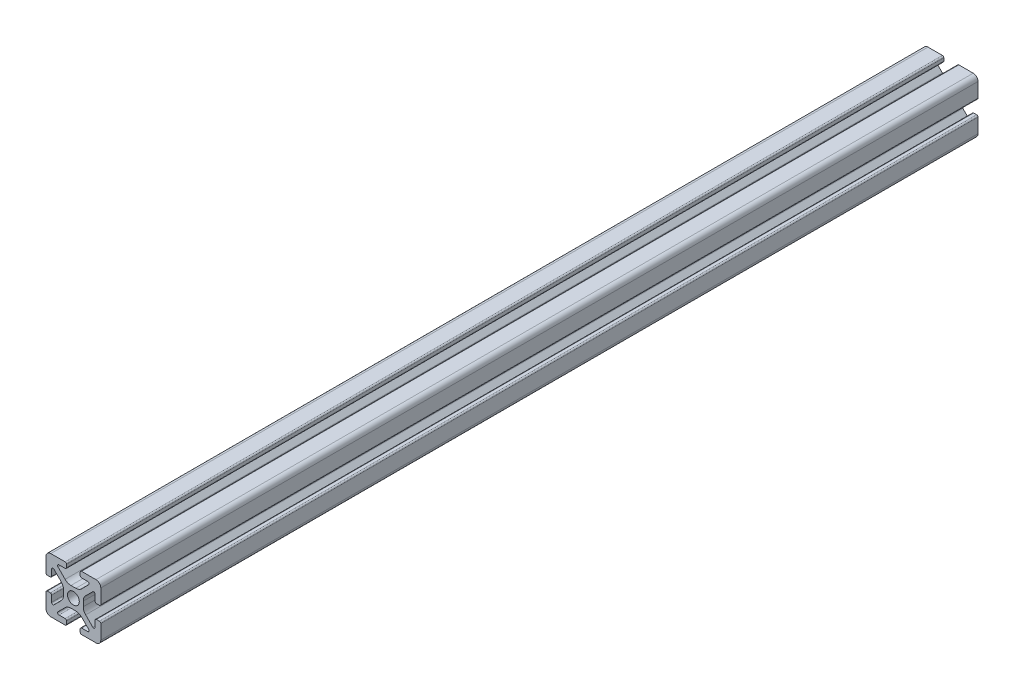
SolidWorks part; units mm, degrees
material "1060 Alloy"
ref_plane "Front Plane" through (0, 0, 0) normal (0, 0, 1) x (1, 0, 0)
ref_plane "Top Plane" through (0, 0, 0) normal (0, 1, 0) x (1, 0, 0)
ref_plane "Right Plane" through (0, 0, 0) normal (1, 0, 0) x (0, 0, -1)
sketch "Sketch2" plane through (0, 0, 0) normal (0, 0, 1) x (1, 0, 0)
  line L0 (0, 10) -> (0, -10) construction
  line L1 (-10, 0) -> (10, 0) construction
  line L2 (2.5, -10) -> (10, -10)
  line L3 (10, -10) -> (10, -2.5)
  line L4 (2.5, -10) -> (2.5, -7.9246)
  line L5 (2.5, -7.9246) -> (6.4571, -7.9246)
  line L6 (6.4571, -7.9246) -> (2.1325, -3.6)
  line L7 (0, 0) -> (10, -10) construction
  line L8 (10, -2.5) -> (7.9246, -2.5)
  line L9 (7.9246, -2.5) -> (7.9246, -6.4571)
  line L10 (7.9246, -6.4571) -> (3.6, -2.1325)
  line L11 (5.7623, -4.2948) -> (4.2948, -5.7623) construction
  circle A0 centre (0, 0) radius 2.15
  arc A1 (5.25, -7.9246) -> (5.6036, -7.0711) centre (5.25, -7.4246) ccw construction
  point P8 (0, -3.6)
  point P16 (5.0286, -5.0286)
  dimension "Center Hole Diameter" = 4.3
  dimension "D3" = 0.5
  dimension "Rail Height" = 20
  dimension "Rail Width" = 20
  dimension "T-Slot Width" = 5
  dimension "Slot Depth" = 6.4
  dimension "Slot Inner Width" = 11.5
sketch "Sketch3" plane through (0, 0, 0) normal (1, 0, 0) x (0, 0, -1)
  line L0 (-110, -10) -> (110, -10) construction
  line L1 (-84.6, 0) -> (84.6, 0) construction
  line L2 (0, 10) -> (0, -10) construction
  line L3 (0, 10) -> (0, -10) construction
  point P6 (-84.6, 0)
  point P8 (84.6, 0)
  dimension "Length" = 220
  dimension "D1" = 25.4
sketch "Sketch4" plane through (0, 0, 0) normal (0, 0, 1) x (1, 0, 0)
  line L0 (3, -10) -> (8.25, -10)
  line L1 (2.5, -10) -> (10, -10) construction
  line L2 (2.5, -10) -> (2.5, -7.9246) construction
  line L3 (2.5, -7.9246) -> (6.4571, -7.9246) construction
  line L4 (2.5, -8.4246) -> (2.5, -9.5)
  line L5 (3, -7.9246) -> (5.25, -7.9246)
  line L6 (0, -3.6) -> (0.8898, -3.6)
  line L7 (6.4571, -7.9246) -> (2.1325, -3.6) construction
  line L8 (3.0112, -4.4787) -> (5.6036, -7.0711)
  line L9 (10, -10) -> (10, -2.5) construction
  line L10 (7.9246, -6.4571) -> (3.6, -2.1325) construction
  line L11 (7.9246, -2.5) -> (7.9246, -6.4571) construction
  line L12 (7.9246, -5.25) -> (7.9246, -3)
  line L13 (10, -2.5) -> (7.9246, -2.5) construction
  line L14 (8.4246, -2.5) -> (9.5, -2.5)
  line L15 (10, -3) -> (10, -8.25)
  line L16 (7.0711, -5.6036) -> (4.4787, -3.0112)
  line L17 (3.6, 0) -> (3.6, -0.8898)
  line L18 (-10, 0) -> (10, 0) construction
  line L19 (0, -3.6) -> (0, -2.15)
  line L20 (0, 10) -> (0, -10) construction
  line L21 (3.6, 0) -> (2.15, 0)
  arc A0 (2.5, -9.5) -> (3, -10) centre (3, -9.5) ccw
  arc A1 (5.25, -7.9246) -> (5.6036, -7.0711) centre (5.25, -7.4246) ccw construction
  arc A2 (2.5, -8.4246) -> (3, -7.9246) centre (3, -8.4246) cw
  arc A3 (5.25, -7.9246) -> (5.6036, -7.0711) centre (5.25, -7.4246) ccw
  arc A4 (0.8898, -3.6) -> (3.0112, -4.4787) centre (0.8898, -6.6) cw
  arc A5 (8.25, -10) -> (10, -8.25) centre (8.25, -8.25) ccw
  arc A6 (7.0711, -5.6036) -> (7.9246, -5.25) centre (7.4246, -5.25) ccw
  arc A7 (7.9246, -3) -> (8.4246, -2.5) centre (8.4246, -3) cw
  arc A8 (9.5, -2.5) -> (10, -3) centre (9.5, -3) cw
  arc A9 (4.4787, -3.0112) -> (3.6, -0.8898) centre (6.6, -0.8898) cw
  circle A10 centre (0, 0) radius 2.15 construction
  arc A11 (0, -2.15) -> (2.15, 0) centre (0, 0) ccw
  dimension "D1" = 1.75
  dimension "D2" = 3
extrude "Boss-Extrude1" add sketch "Sketch4" along normal mid plane 322.6666
mirror "Mirror1" about plane through (0, 0, 0) normal (1, 0, 0) of bodies 134
mirror "Mirror2" about plane through (0, 0, 0) normal (0, 1, 0) of bodies 135
sketch "Sketch5" plane through (0, 0, 161.3333) normal (0, 0, 1) x (1, 0, 0)
  line L1 (-13.9539, 12.3566) -> (13.8334, 12.3566)
  line L2 (-13.9539, 12.3566) -> (-13.9539, -13.6827)
  line L3 (-13.9539, -13.6827) -> (13.8334, -13.6827)
  line L4 (13.8334, 12.3566) -> (13.8334, -13.6827)
extrude "Cut-Extrude1" cut sketch "Sketch5" against normal blind 2.4
equation "\"D3@Sketch2\"=\"T-Slot Width@Sketch2\"*0.1"
equation "\"D1@Sketch4\"=\"D3@Sketch2\"*3.5"
equation "\"D2@Sketch4\"=\"D3@Sketch2\"*6"
equation "\"D1@Boss-Extrude1\"= \"Length@Sketch3\" * 16.13333 / 11"
